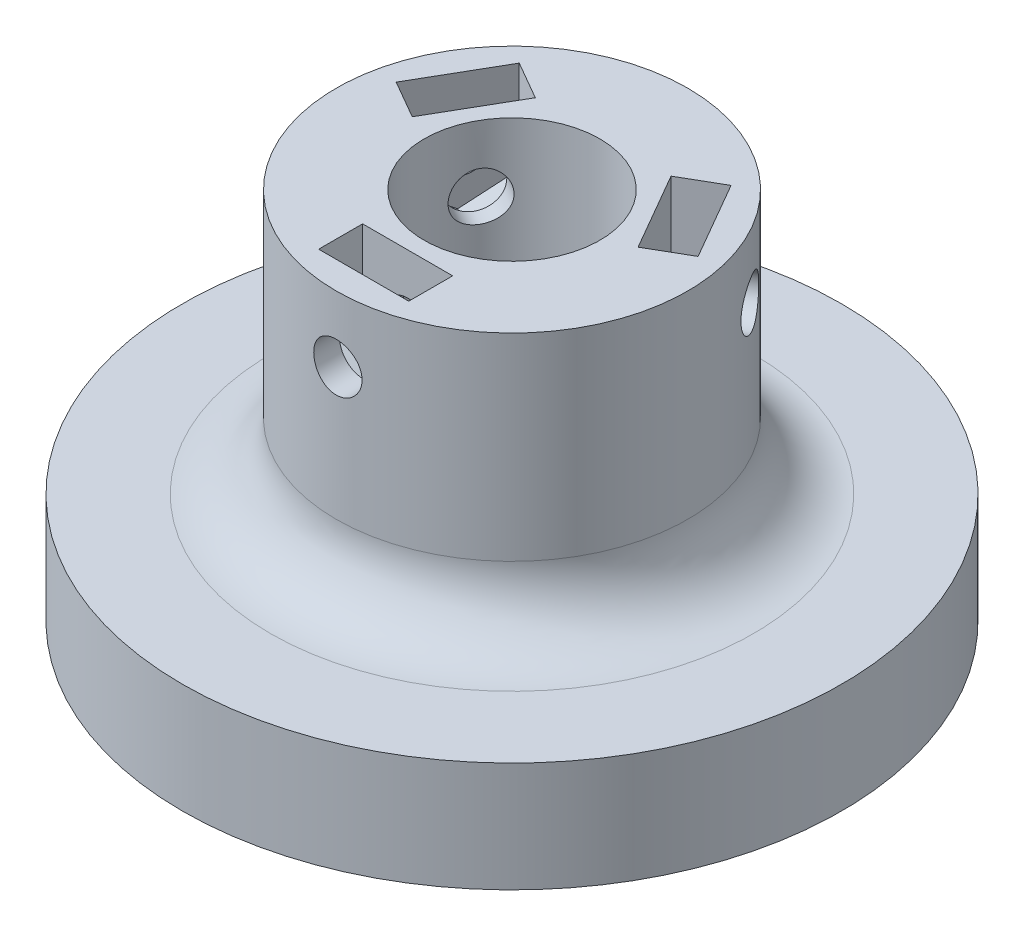
SolidWorks part; units mm, degrees
ref_plane "Front Plane" through (0, 0, 0) normal (0, 0, 1) x (1, 0, 0)
ref_plane "Top Plane" through (0, 0, 0) normal (0, 1, 0) x (1, 0, 0)
ref_plane "Right Plane" through (0, 0, 0) normal (1, 0, 0) x (0, 0, -1)
sketch "Sketch1" plane through (0, 0, 0) normal (0, 0, 1) x (1, 0, 0)
  line L0 (0, 0) -> (0, 15.8) construction
  line L2 (0, 0) -> (15, 0)
  line L3 (15, 0) -> (15, 5)
  line L4 (15, 5) -> (8, 5)
  line L5 (8, 5) -> (8, 17)
  line L6 (8, 17) -> (4, 17)
  line L7 (4, 17) -> (4, 5)
  line L8 (4, 5) -> (0, 5)
  line L9 (0, 5) -> (0, 0)
  dimension "D1" = 8
  dimension "D2" = 30
  dimension "D3" = 5
  dimension "D4" = 17
  dimension "D5" = 4
  dimension "D6" = 12
revolve "Revolve1" add sketch "Sketch1" angle 360 about L0
hole_wizard "M2 Clearance Hole1" positions "Sketch2" profile "Sketch4" hole size "M2" standard "ISO"
sketch "Sketch2" plane through (0, 0, 0) normal (0, 0, 1) x (1, 0, 0)
  line L0 (0, 17) -> (0, 5) construction
  line L1 (8, 17) -> (-8, 17) construction
  line L2 (15, 5) -> (-15, 5) construction
  point P0 (0, 14)
  dimension "D1" = 3
sketch "Sketch4" plane through (0, 14, 0) normal (1, 0, 0) x (0, 1, 0)
  line L0 (0, 0) -> (0, 20.4904)
  line L1 (0, 20.4904) -> (1.1, 20.4904)
  line L2 (1.1, 20.4904) -> (1.1, 0)
  line L5 (1.1, 0) -> (0, 0)
  line L11 (0, -6.35) -> (0, 107.95) construction
  dimension "Thru Hole Dia." = 2.2
  dimension "Thru Hole Depth" = 20.4904
ref_plane "Plane1" through (0, 0, 8) normal (0, 0, 1) x (1, 0, 0)
sketch "Sketch5" plane through (0, 0, 8) normal (0, 0, 1) x (1, 0, 0)
  line L0 (-2.05, 15.1836) -> (-2.05, 17)
  line L1 (2.05, 15.1836) -> (0, 16.3671)
  line L2 (0, 16.3671) -> (-2.05, 15.1836)
  line L3 (-2.05, 15.1836) -> (-2.05, 12.8164)
  line L4 (-2.05, 12.8164) -> (0, 11.6329)
  line L5 (0, 11.6329) -> (2.05, 12.8164)
  line L6 (2.05, 12.8164) -> (2.05, 15.1836)
  line L7 (4, 17) -> (-4, 17) construction
  line L8 (-2.05, 17) -> (2.05, 17)
  line L9 (2.05, 17) -> (2.05, 15.1836)
  circle A0 centre (0, 14) radius 2.05 construction
  dimension "D1" = 4.1
extrude "Cut-Extrude1" cut sketch "Sketch5" against normal blind 2 from offset 1.25 contours L9 L8 L0 L2 L1 | L5 L6 L1 L2 L3 L4 offset against normal yes
pattern_circular "CirPattern1" count 3 over 360 about axis through (0, 0, 0) along (0, 1, 0) of "M2 Clearance Hole1", "Cut-Extrude1"
fillet "Fillet1" radius 3 1 edges at (0, 5, -8)
